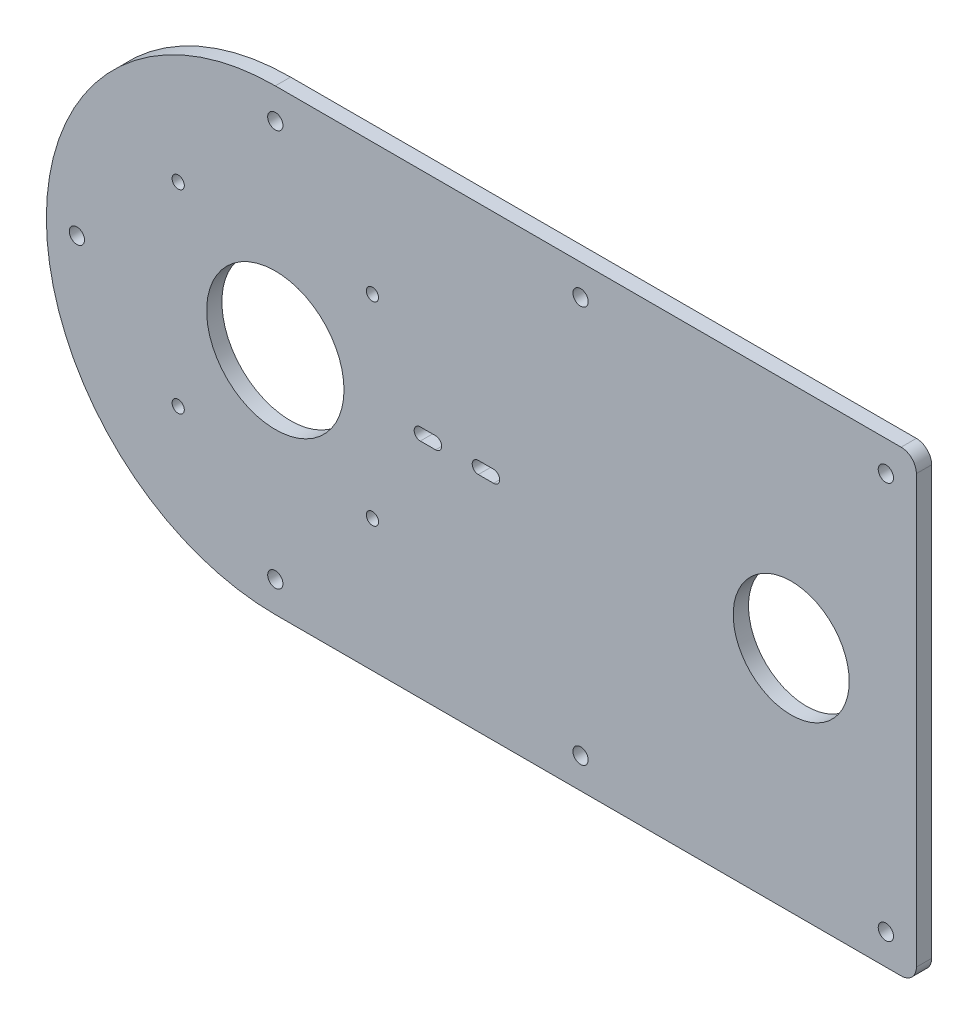
SolidWorks part; units mm, degrees
ref_plane "Front Plane" through (0, 0, 0) normal (0, 0, 1) x (1, 0, 0)
ref_plane "Top Plane" through (0, 0, 0) normal (0, 1, 0) x (1, 0, 0)
ref_plane "Right Plane" through (0, 0, 0) normal (1, 0, 0) x (0, 0, -1)
sketch "Sketch1" plane through (0, 0, 0) normal (0, 0, 1) x (1, 0, 0)
  line L1 (30.0007, 92.5455) -> (235.0007, 92.5455)
  line L3 (30.0007, -57.4545) -> (235.0007, -57.4545)
  line L4 (240.0007, 87.5455) -> (240.0007, -52.4545)
  line L5 (77.5007, 19.5455) -> (82.5007, 19.5455)
  line L6 (77.5007, 15.5455) -> (82.5007, 15.5455)
  line L7 (101.5007, 19.5455) -> (96.5007, 19.5455)
  line L8 (101.5007, 15.5455) -> (96.5007, 15.5455)
  arc A0 (235.0007, -57.4545) -> (240.0007, -52.4545) centre (235.0007, -52.4545) ccw
  arc A1 (235.0007, 92.5455) -> (240.0007, 87.5455) centre (235.0007, 87.5455) cw
  arc A2 (30.0007, 92.5455) -> (30.0007, -57.4545) centre (30.0007, 17.5455) ccw
  circle A7 centre (-34.9993, 17.5455) radius 2.5
  circle A10 centre (30.0007, -47.4545) radius 2.5
  circle A11 centre (30.0007, 82.5455) radius 2.5
  circle A12 centre (230.0007, -47.4545) radius 2.5
  circle A13 centre (230.0007, 82.5455) radius 2.5
  circle A15 centre (130.0007, 82.5455) radius 2.5
  circle A16 centre (130.0007, -47.4545) radius 2.5
  circle A17 centre (199.0007, 17.5455) radius 19
  circle A18 centre (30.0007, 17.5455) radius 22.5
  arc A19 (77.5007, 19.5455) -> (77.5007, 15.5455) centre (77.5007, 17.5455) ccw
  arc A20 (82.5007, 15.5455) -> (82.5007, 19.5455) centre (82.5007, 17.5455) ccw
  arc A21 (101.5007, 15.5455) -> (101.5007, 19.5455) centre (101.5007, 17.5455) ccw
  arc A22 (96.5007, 19.5455) -> (96.5007, 15.5455) centre (96.5007, 17.5455) ccw
  circle A23 centre (61.8157, 49.3605) radius 2
  circle A24 centre (61.8157, -14.2695) radius 2
  circle A25 centre (-1.8143, -14.2695) radius 2
  circle A26 centre (-1.8143, 49.3605) radius 2
  point P2 (30.0007, 17.5455)
  point P14 (30.0007, 17.5455)
  point P21 (-34.9993, 17.5455)
  point P49 (30.0007, 17.5455)
  dimension "D1" = 5
  dimension "D2" = 38
  dimension "D3" = 45
  dimension "D4" = 5
  dimension "D5" = 5
  dimension "D6" = 5
  dimension "D7" = 5
  dimension "D8" = 5
  dimension "D9" = 5
  dimension "D10" = 5
  dimension "D11" = 4
  dimension "D12" = 4
  dimension "D13" = 4
  dimension "D14" = 4
extrude "Boss-Extrude1" add sketch "Sketch1" along normal blind 5
